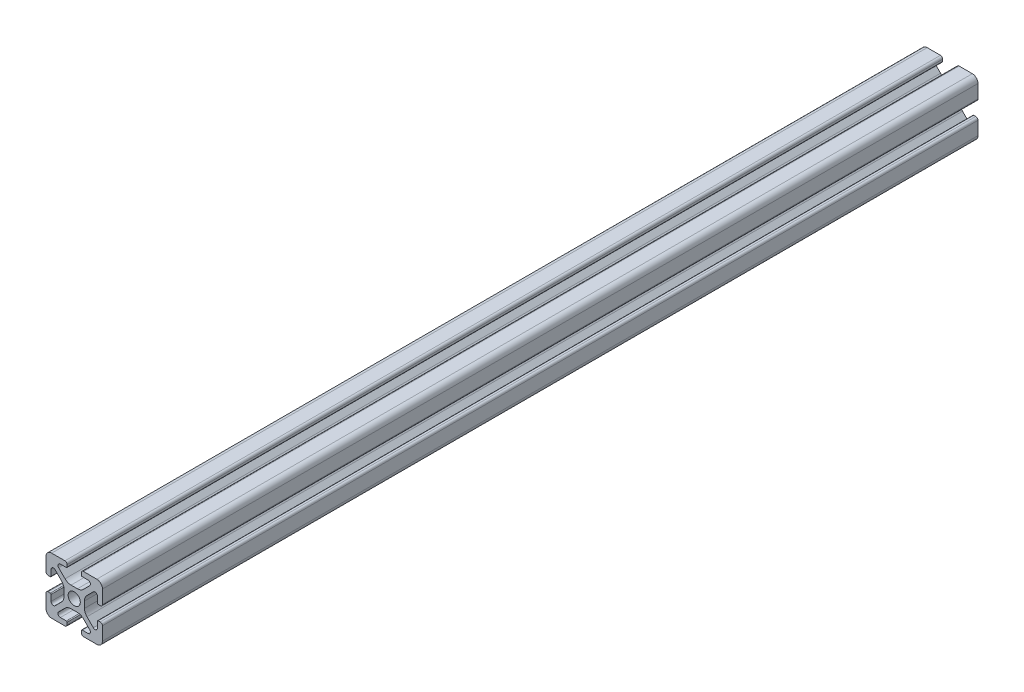
SolidWorks part; units mm, degrees
ref_plane "Front Plane" through (0, 0, 0) normal (0, 0, 1) x (1, 0, 0)
ref_plane "Top Plane" through (0, 0, 0) normal (0, 1, 0) x (1, 0, 0)
ref_plane "Right Plane" through (0, 0, 0) normal (1, 0, 0) x (0, 0, -1)
sketch "Sketch1" plane through (0, 0, 0) normal (0, 0, 1) x (1, 0, 0)
  line L2 (-9.9949, 7.9883) -> (-9.9949, 3.2893)
  line L3 (-7.9883, 9.9949) -> (-3.2893, 9.9949)
  line L4 (-2.5019, 9.2075) -> (-2.5019, 8.4963)
  line L5 (-2.8067, 8.1915) -> (-4.9149, 8.1915)
  line L6 (-5.5076, 6.7606) -> (-3.2528, 4.5058)
  line L7 (-6.7606, 5.5076) -> (-4.5058, 3.2528)
  line L8 (-8.1915, 4.9149) -> (-8.1915, 2.8067)
  line L9 (-8.4963, 2.5019) -> (-9.2075, 2.5019)
  line L11 (-1.1334, 3.6279) -> (1.1334, 3.6279)
  line L12 (-3.6279, 1.1334) -> (-3.6279, -1.1334)
  line L13 (8.4963, 2.5019) -> (9.2075, 2.5019)
  line L14 (8.1915, 4.9149) -> (8.1915, 2.8067)
  line L15 (9.9949, 7.9883) -> (9.9949, 3.2893)
  line L16 (7.9883, 9.9949) -> (3.2893, 9.9949)
  line L17 (2.5019, 9.2075) -> (2.5019, 8.4963)
  line L18 (2.8067, 8.1915) -> (4.9149, 8.1915)
  line L19 (3.6279, 1.1334) -> (3.6279, -1.1334)
  line L20 (5.5076, 6.7606) -> (3.2528, 4.5058)
  line L21 (6.7606, 5.5076) -> (4.5058, 3.2528)
  line L22 (-8.4963, -2.5019) -> (-9.2075, -2.5019)
  line L23 (-8.1915, -4.9149) -> (-8.1915, -2.8067)
  line L24 (-6.7606, -5.5076) -> (-4.5058, -3.2528)
  line L25 (-5.5076, -6.7606) -> (-3.2528, -4.5058)
  line L26 (-2.8067, -8.1915) -> (-4.9149, -8.1915)
  line L27 (-2.5019, -9.2075) -> (-2.5019, -8.4963)
  line L28 (-7.9883, -9.9949) -> (-3.2893, -9.9949)
  line L29 (-9.9949, -7.9883) -> (-9.9949, -3.2893)
  line L30 (9.9949, -7.9883) -> (9.9949, -3.2893)
  line L31 (7.9883, -9.9949) -> (3.2893, -9.9949)
  line L32 (2.5019, -9.2075) -> (2.5019, -8.4963)
  line L33 (2.8067, -8.1915) -> (4.9149, -8.1915)
  line L34 (5.5076, -6.7606) -> (3.2528, -4.5058)
  line L35 (6.7606, -5.5076) -> (4.5058, -3.2528)
  line L36 (8.1915, -4.9149) -> (8.1915, -2.8067)
  line L37 (8.4963, -2.5019) -> (9.2075, -2.5019)
  line L38 (-1.1334, -3.6279) -> (1.1334, -3.6279)
  circle A0 centre (0, 0) radius 2.1463
  arc A1 (-9.9949, 7.9883) -> (-7.9883, 9.9949) centre (-7.9883, 7.9883) cw
  arc A2 (-6.7606, 5.5076) -> (-8.1915, 4.9149) centre (-7.3533, 4.9149) ccw
  arc A3 (-4.9149, 8.1915) -> (-5.5076, 6.7606) centre (-4.9149, 7.3533) ccw
  arc A4 (-3.2893, 9.9949) -> (-2.5019, 9.2075) centre (-3.2893, 9.2075) cw
  arc A5 (-9.9949, 3.2893) -> (-9.2075, 2.5019) centre (-9.2075, 3.2893) ccw
  arc A6 (-8.1915, 2.8067) -> (-8.4963, 2.5019) centre (-8.4963, 2.8067) cw
  arc A7 (-2.5019, 8.4963) -> (-2.8067, 8.1915) centre (-2.8067, 8.4963) cw
  arc A8 (-1.1334, 3.6279) -> (-3.2528, 4.5058) centre (-1.1334, 6.6251) cw
  arc A9 (-3.6279, 1.1334) -> (-4.5058, 3.2528) centre (-6.6251, 1.1334) ccw
  arc A10 (8.1915, 2.8067) -> (8.4963, 2.5019) centre (8.4963, 2.8067) ccw
  arc A11 (9.9949, 3.2893) -> (9.2075, 2.5019) centre (9.2075, 3.2893) cw
  arc A12 (9.9949, 7.9883) -> (7.9883, 9.9949) centre (7.9883, 7.9883) ccw
  arc A13 (3.2893, 9.9949) -> (2.5019, 9.2075) centre (3.2893, 9.2075) ccw
  arc A14 (2.5019, 8.4963) -> (2.8067, 8.1915) centre (2.8067, 8.4963) ccw
  arc A15 (1.1334, 3.6279) -> (3.2528, 4.5058) centre (1.1334, 6.6251) ccw
  arc A16 (3.6279, 1.1334) -> (4.5058, 3.2528) centre (6.6251, 1.1334) cw
  arc A17 (6.7606, 5.5076) -> (8.1915, 4.9149) centre (7.3533, 4.9149) cw
  arc A18 (4.9149, 8.1915) -> (5.5076, 6.7606) centre (4.9149, 7.3533) cw
  arc A19 (-3.6279, -1.1334) -> (-4.5058, -3.2528) centre (-6.6251, -1.1334) cw
  arc A20 (-1.1334, -3.6279) -> (-3.2528, -4.5058) centre (-1.1334, -6.6251) ccw
  arc A21 (-2.5019, -8.4963) -> (-2.8067, -8.1915) centre (-2.8067, -8.4963) ccw
  arc A22 (-8.1915, -2.8067) -> (-8.4963, -2.5019) centre (-8.4963, -2.8067) ccw
  arc A23 (-9.9949, -3.2893) -> (-9.2075, -2.5019) centre (-9.2075, -3.2893) cw
  arc A24 (-3.2893, -9.9949) -> (-2.5019, -9.2075) centre (-3.2893, -9.2075) ccw
  arc A25 (-4.9149, -8.1915) -> (-5.5076, -6.7606) centre (-4.9149, -7.3533) cw
  arc A26 (-6.7606, -5.5076) -> (-8.1915, -4.9149) centre (-7.3533, -4.9149) cw
  arc A27 (-9.9949, -7.9883) -> (-7.9883, -9.9949) centre (-7.9883, -7.9883) ccw
  arc A28 (9.9949, -7.9883) -> (7.9883, -9.9949) centre (7.9883, -7.9883) cw
  arc A29 (6.7606, -5.5076) -> (8.1915, -4.9149) centre (7.3533, -4.9149) ccw
  arc A30 (4.9149, -8.1915) -> (5.5076, -6.7606) centre (4.9149, -7.3533) ccw
  arc A31 (3.2893, -9.9949) -> (2.5019, -9.2075) centre (3.2893, -9.2075) cw
  arc A32 (9.9949, -3.2893) -> (9.2075, -2.5019) centre (9.2075, -3.2893) ccw
  arc A33 (8.1915, -2.8067) -> (8.4963, -2.5019) centre (8.4963, -2.8067) cw
  arc A34 (2.5019, -8.4963) -> (2.8067, -8.1915) centre (2.8067, -8.4963) cw
  arc A35 (1.1334, -3.6279) -> (3.2528, -4.5058) centre (1.1334, -6.6251) cw
  arc A36 (3.6279, -1.1334) -> (4.5058, -3.2528) centre (6.6251, -1.1334) ccw
extrude "Boss-Extrude1" add sketch "Sketch1" along normal mid plane 310
